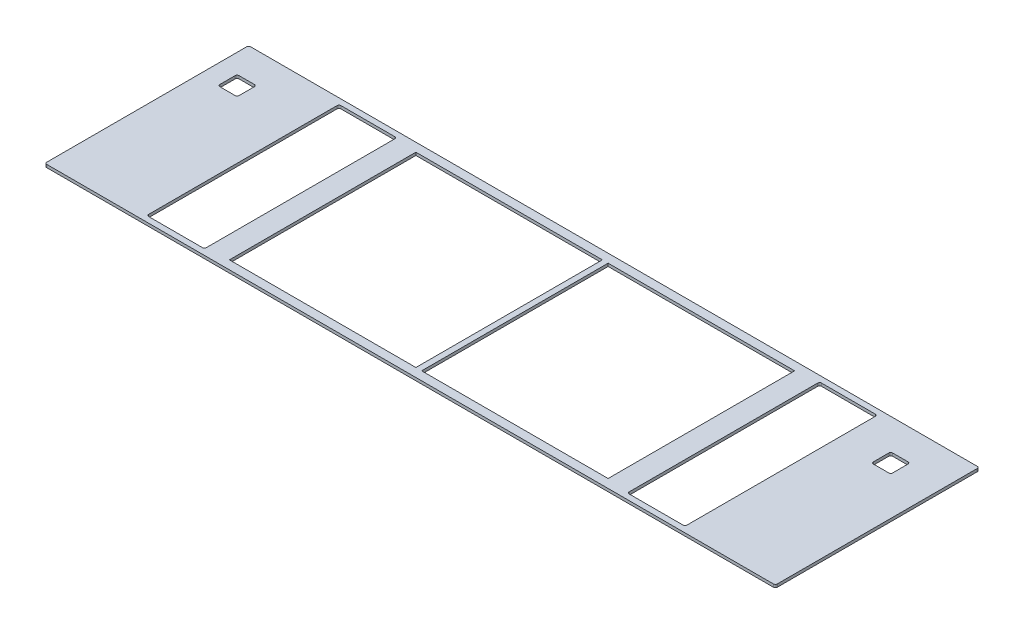
SolidWorks part; units mm, degrees
ref_plane "前视基准面" through (0, 0, 0) normal (0, 0, 1) x (1, 0, 0)
ref_plane "上视基准面" through (0, 0, 0) normal (0, 1, 0) x (1, 0, 0)
ref_plane "右视基准面" through (0, 0, 0) normal (1, 0, 0) x (0, 0, -1)
sketch "草图1" plane through (0, 0, 0) normal (0, 1, 0) x (1, 0, 0)
  line L5 (577, 9) -> (383, 9)
  line L6 (577, 9) -> (577, 203)
  line L7 (577, 203) -> (383, 203)
  line L8 (383, 9) -> (383, 203)
  line L9 (377, 9) -> (183, 9)
  line L10 (377, 9) -> (377, 203)
  line L11 (377, 203) -> (183, 203)
  line L12 (183, 9) -> (183, 203)
  line L28 (383, 81) -> (377, 81)
  line L78 (2, 0) -> (758, 0)
  line L79 (760, 2) -> (760, 210)
  line L80 (758, 212) -> (2, 212)
  line L81 (0, 210) -> (0, 2)
  line L82 (658, 6) -> (602, 6)
  line L83 (660, 8) -> (660, 204)
  line L84 (658, 206) -> (602, 206)
  line L85 (600, 8) -> (600, 204)
  line L86 (158, 6) -> (102, 6)
  line L87 (160, 8) -> (160, 204)
  line L88 (158, 206) -> (102, 206)
  line L89 (100, 8) -> (100, 204)
  line L90 (718, 160) -> (702, 160)
  line L91 (720, 162) -> (720, 178)
  line L92 (718, 180) -> (702, 180)
  line L93 (700, 162) -> (700, 178)
  line L94 (38, 160) -> (22, 160)
  line L95 (40, 162) -> (40, 178)
  line L96 (38, 180) -> (22, 180)
  line L97 (20, 162) -> (20, 178)
  arc A28 (2, 212) -> (0, 210) centre (2, 210) ccw
  arc A29 (0, 2) -> (2, 0) centre (2, 2) ccw
  arc A30 (758, 212) -> (760, 210) centre (758, 210) cw
  arc A31 (760, 2) -> (758, 0) centre (758, 2) cw
  arc A32 (602, 6) -> (600, 8) centre (602, 8) cw
  arc A33 (660, 8) -> (658, 6) centre (658, 8) cw
  arc A34 (602, 206) -> (600, 204) centre (602, 204) ccw
  arc A35 (658, 206) -> (660, 204) centre (658, 204) cw
  arc A36 (700, 162) -> (702, 160) centre (702, 162) ccw
  arc A37 (702, 180) -> (700, 178) centre (702, 178) ccw
  arc A38 (718, 180) -> (720, 178) centre (718, 178) cw
  arc A39 (720, 162) -> (718, 160) centre (718, 162) cw
  arc A40 (160, 204) -> (158, 206) centre (158, 204) ccw
  arc A41 (158, 6) -> (160, 8) centre (158, 8) ccw
  arc A42 (102, 6) -> (100, 8) centre (102, 8) cw
  arc A43 (102, 206) -> (100, 204) centre (102, 204) ccw
  arc A44 (22, 160) -> (20, 162) centre (22, 162) cw
  arc A45 (22, 180) -> (20, 178) centre (22, 178) ccw
  arc A46 (40, 178) -> (38, 180) centre (38, 178) ccw
  arc A47 (38, 160) -> (40, 162) centre (38, 162) ccw
  point P17 (0, 0)
  point P20 (760, 212)
  point P23 (760, 0)
  point P41 (600, 6)
  point P44 (660, 6)
  point P47 (600, 206)
  point P52 (700, 160)
  point P57 (720, 180)
  point P60 (720, 160)
  point P65 (160, 206)
  point P68 (160, 6)
  point P71 (100, 6)
  point P76 (20, 160)
  point P81 (40, 180)
  point P84 (40, 160)
  dimension "D3" = 760
  dimension "D4" = 212
  dimension "D7" = 6
  dimension "D10" = 200
  dimension "D13" = 23
  dimension "D20" = 20
  dimension "D23" = 20
  dimension "D30" = 2
  dimension "D5" = 9
  dimension "D6" = 9
  dimension "D19" = 2
  dimension "D31" = 2
  dimension "D8" = 183
  dimension "D9" = 23
  dimension "D11" = 6
  dimension "D12" = 60
  dimension "D14" = 60
  dimension "D15" = 200
  dimension "D16" = 194
  dimension "D17" = 194
  dimension "D18" = 6
  dimension "D21" = 20
  dimension "D22" = 20
  dimension "D24" = 160
  dimension "D25" = 40
  dimension "D26" = 194
  dimension "D27" = 194
  dimension "D28" = 160
  dimension "D29" = 20
extrude "凸台-拉伸1" add sketch "草图1" against normal blind 3
